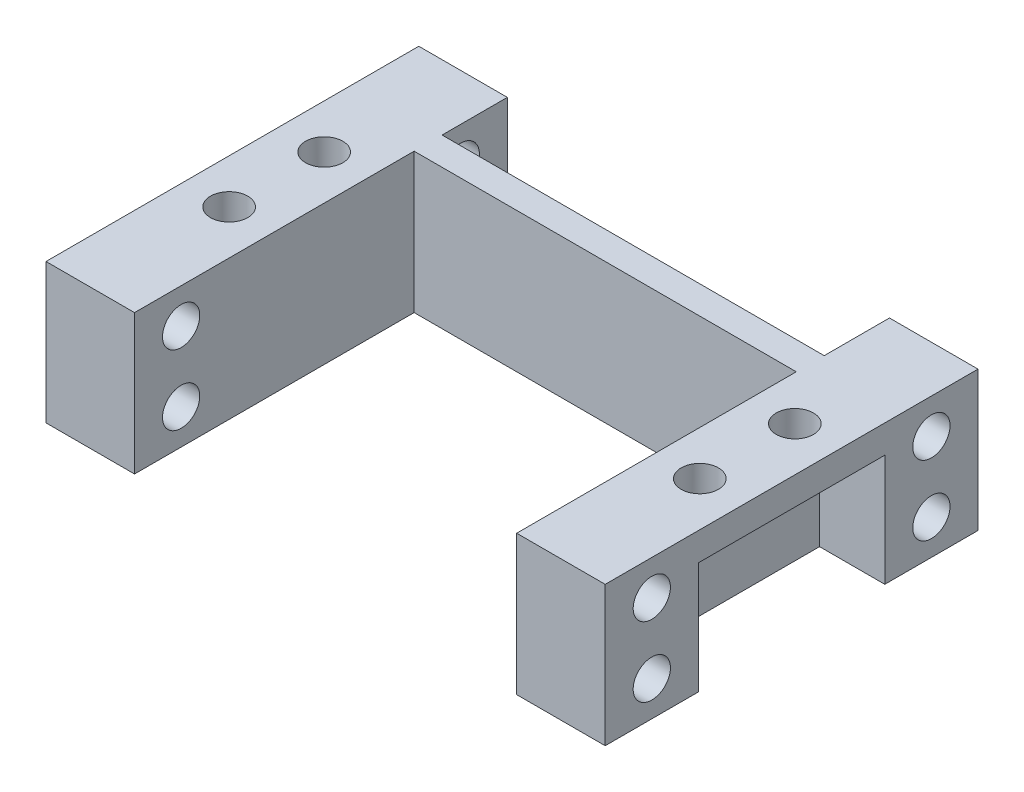
SolidWorks part; units mm, degrees
ref_plane "Front Plane" through (0, 0, 0) normal (0, 0, 1) x (1, 0, 0)
ref_plane "Top Plane" through (0, 0, 0) normal (0, 1, 0) x (1, 0, 0)
ref_plane "Right Plane" through (0, 0, 0) normal (1, 0, 0) x (0, 0, -1)
sketch "Sketch1" plane through (0, 0, 0) normal (0, 0, 1) x (1, 0, 0)
  line L1 (0, 0) -> (46, 0)
  line L2 (0, 0) -> (0, 15)
  line L3 (0, 15) -> (46, 15)
  line L4 (46, 0) -> (46, 15)
  dimension "D1" = 46
  dimension "D2" = 15
extrude "Boss-Extrude1" add sketch "Sketch1" along normal blind 3
sketch "Sketch3" plane through (0, 0, 3) normal (0, 0, 1) x (1, 0, 0)
  line L1 (0, 0) -> (2.5, 0)
  line L2 (0, 0) -> (0, 15)
  line L3 (0, 15) -> (2.5, 15)
  line L4 (2.5, 0) -> (2.5, 15)
  dimension "D1" = 15
  dimension "D2" = 2.5
extrude "Boss-Extrude2" add sketch "Sketch3" along normal blind 20
sketch "Sketch4" plane through (0, 0, 0) normal (-1, 0, 0) x (0, 0, 1)
  line L1 (23, 15) -> (3, 15)
  line L2 (23, 15) -> (23, 12)
  line L3 (23, 12) -> (3, 12)
  line L4 (3, 15) -> (3, 12)
  dimension "D1" = 3
  dimension "D2" = 20
extrude "Boss-Extrude3" add sketch "Sketch4" along normal blind 7
sketch "Sketch5" plane through (0, 15, 0) normal (0, 1, 0) x (1, 0, 0)
  line L0 (0, -3) -> (0, -23) construction
  line L1 (-2.25, -23) -> (-2.25, -20.35) construction
  line L2 (2.5, -23) -> (-7, -23) construction
  line L3 (-2.25, -23) -> (0, -23) construction
  line L4 (-7, -13) -> (2.5, -13) construction
  line L5 (-7, -23) -> (-7, -3) construction
  line L6 (2.5, -23) -> (2.5, -3) construction
  circle A0 centre (-2.25, -18.1) radius 2.25 construction
  circle A1 centre (-2.25, -18.1) radius 2
  circle A2 centre (-2.25, -7.9) radius 2
  dimension "D2" = 4.5
  dimension "D4" = 4
  dimension "D1" = 2.65
  dimension "D3" = 2.25
extrude "Cut-Extrude1" cut sketch "Sketch5" against normal blind 7
ref_plane "Plane1" through (23, 0, 0) normal (1, 0, 0) x (0, 0, -1)
mirror "Mirror1" about plane through (23, 0, 0) normal (1, 0, 0) of "Boss-Extrude2", "Boss-Extrude3", "Cut-Extrude1"
ref_plane "Plane2" through (-7, 12, 23) normal (0, 1, 0) x (1, 0, 0)
sketch "Sketch7" plane through (0, 0, 23) normal (0, 0, 1) x (1, 0, 0)
  line L1 (2.5, 15) -> (-7, 15)
  line L2 (2.5, 15) -> (2.5, 0)
  line L3 (2.5, 0) -> (-7, 0)
  line L4 (-7, 15) -> (-7, 0)
  dimension "D1" = 9.5
extrude "Boss-Extrude4" add sketch "Sketch7" along normal blind 10
sketch "Sketch8" plane through (-7, 0, 0) normal (-1, 0, 0) x (0, 0, 1)
  line L0 (28, 0) -> (28, 15) construction
  line L1 (33, 0) -> (23, 0) construction
  line L2 (33, 15) -> (3, 15) construction
  line L3 (33, 7.5) -> (23, 7.5) construction
  line L4 (33, 15) -> (33, 0) construction
  line L5 (23, 12) -> (23, 0) construction
  circle A0 centre (28, 11.25) radius 2
  circle A1 centre (28, 3.75) radius 2
  dimension "D1" = 4
  dimension "D2" = 3.75
extrude "Cut-Extrude2" cut sketch "Sketch8" against normal blind 10
mirror "Mirror2" about plane through (23, 0, 0) normal (1, 0, 0) of "Boss-Extrude4", "Cut-Extrude2"
ref_plane "Plane3" through (0, 0, 13) normal (0, 0, 1) x (1, 0, 0)
mirror "Mirror3" about plane through (0, 0, 13) normal (0, 0, 1) of "Mirror2", "Cut-Extrude2", "Boss-Extrude4"
